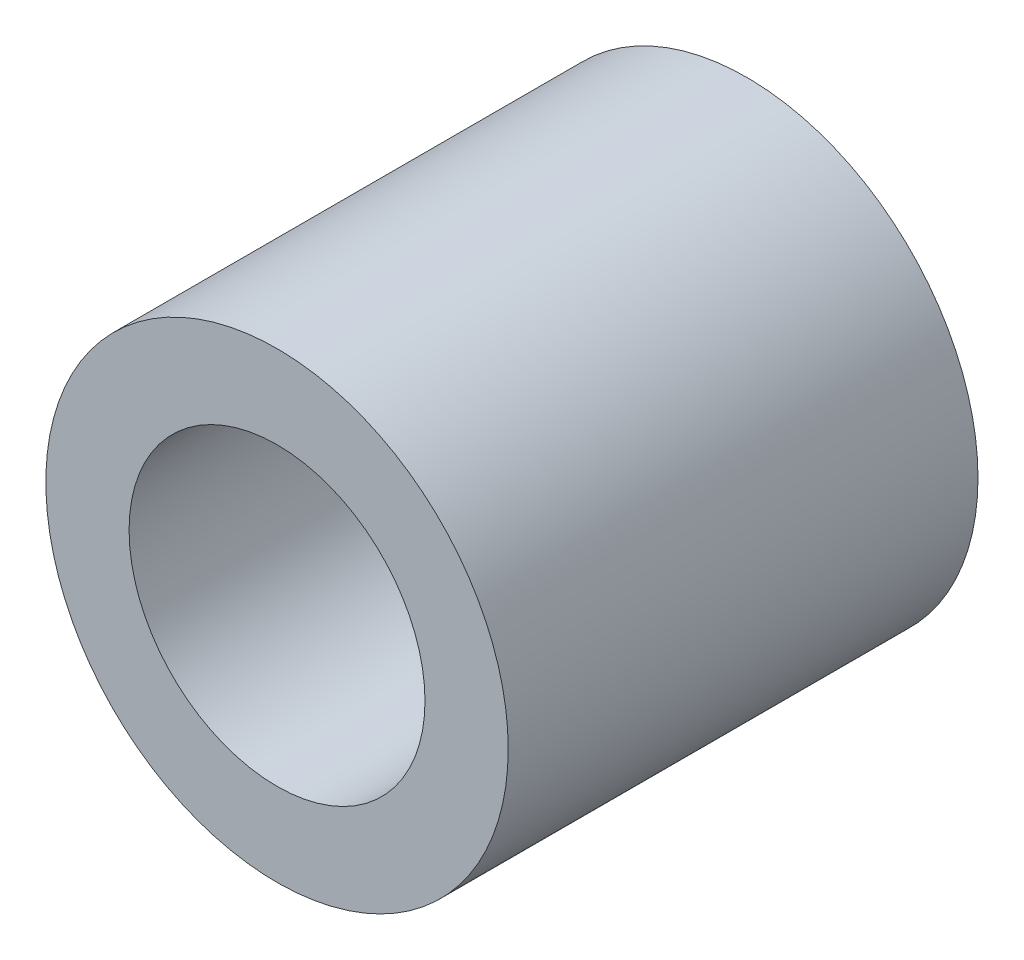
SolidWorks part; units mm, degrees
ref_plane "Front Plane" through (0, 0, 0) normal (0, 0, 1) x (1, 0, 0)
ref_plane "Top Plane" through (0, 0, 0) normal (0, 1, 0) x (1, 0, 0)
ref_plane "Right Plane" through (0, 0, 0) normal (1, 0, 0) x (0, 0, -1)
sketch "Sketch1" plane through (0, 0, 0) normal (0, 0, 1) x (1, 0, 0)
  circle A0 centre (0, 0) radius 1.6
  circle A1 centre (0, 0) radius 2.5
  dimension "D1" = 3.2
  dimension "D2" = 5
extrude "Boss-Extrude1" add sketch "Sketch1" along normal blind 5.08
